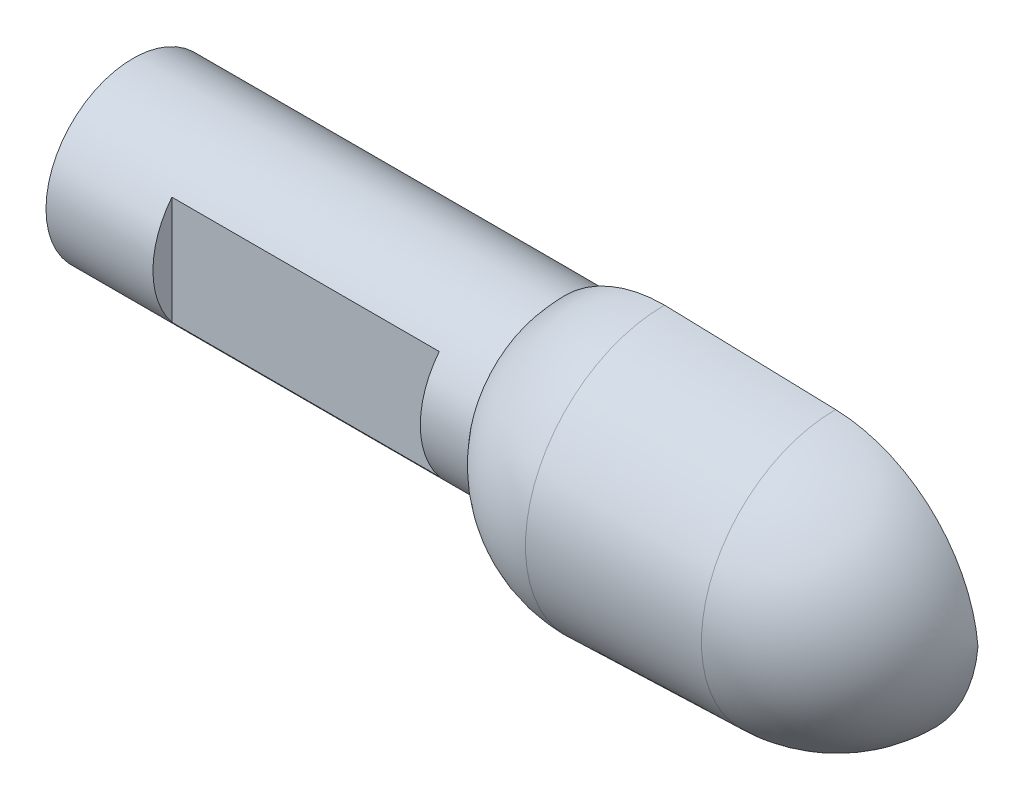
SolidWorks part; units mm, degrees
ref_plane "Front Plane" through (0, 0, 0) normal (0, 0, 1) x (1, 0, 0)
ref_plane "Top Plane" through (0, 0, 0) normal (0, 1, 0) x (1, 0, 0)
ref_plane "Right Plane" through (0, 0, 0) normal (1, 0, 0) x (0, 0, -1)
sketch "Sketch1" plane through (0, 0, 0) normal (0, 0, 1) x (1, 0, 0)
  line L0 (-6.6315, 0) -> (9.1731, 0)
  line L1 (-6.6315, 0) -> (-6.6315, 1.625)
  line L2 (-6.6315, 1.625) -> (1.2685, 1.625)
  line L3 (-10.8216, 0) -> (-13.7944, 0) construction
  line L4 (3.3101, 2.6) -> (6.5101, 2.5087)
  line L7 (43.6251, -16.8667) -> (43.659, -16.9459)
  line L8 (43.659, -16.9459) -> (43.7293, -17.1459)
  arc A0 (1.2685, 1.625) -> (3.3101, 2.6) centre (3.3101, -0.025) cw
  arc A1 (6.5101, 2.5087) -> (9.1731, 0) centre (6.4316, -0.2424) cw
  dimension "D4" = 2.7522
  dimension "D5" = 2.625
  dimension "D1" = 1.625
  dimension "D2" = 3.2
  dimension "D3" = 7.9
sketch "Sketch2" plane through (0, 0, 0) normal (0, 0, 1) x (1, 0, 0)
  line L0 (-6.6315, 0) -> (-6.6315, 1.625)
  line L1 (-6.6315, 1.625) -> (1.2685, 1.625)
  line L3 (3.3101, 2.6) -> (6.5101, 2.5087)
  line L5 (9.1731, 0) -> (-6.6315, 0)
  line L6 (-13.7944, 0) -> (-10.8216, 0) construction
  arc A0 (1.2685, 1.625) -> (3.3101, 2.6) centre (3.3101, -0.025) cw
  arc A1 (6.5101, 2.5087) -> (9.1731, 0) centre (6.4316, -0.2424) cw
revolve "Revolve1" add sketch "Sketch2" angle 360 about L6
ref_plane "Plane2" through (-6.6315, 0, 0) normal (-1, 0, 0) x (0, 0, 1)
sketch "Sketch8" plane through (-6.6315, 0, 0) normal (-1, 0, 0) x (0, 0, 1)
  line L0 (0, -1.625) -> (0, -2.6)
  line L1 (0, 1.625) -> (0, 2.6)
  circle A0 centre (0, 0) radius 1.625 construction
  circle A1 centre (0, 0) radius 1.625 construction
  circle A2 centre (0, 0) radius 2.6 construction
  arc A3 (0, 1.625) -> (0, -1.625) centre (0, 0) ccw
  arc A4 (0, 2.6) -> (0, -2.6) centre (0, 0) ccw
extrude "Cut-Extrude3" cut sketch "Sketch8" against normal through all
ref_plane "Plane3" through (0, 0, 0) normal (0, 0, -1) x (-1, 0, 0)
sketch "Sketch9" plane through (0, 0, 0) normal (0, 0, -1) x (-1, 0, 0)
  line L1 (-1.2685, 1.625) -> (-1.2685, -1.625)
  line L2 (-1.2685, -1.625) -> (-2.0144, -1.625)
  line L4 (-1.994, 1.625) -> (-1.2685, 1.625)
  line L5 (-7.8593, 1.625) -> (-8.4533, 1.625)
  line L6 (-8.4533, -1.625) -> (-7.8593, -1.625)
  arc A0 (-7.8593, 1.625) -> (-1.994, 1.625) centre (-4.9266, -11.3387) cw
  arc A1 (-7.8593, -1.625) -> (-2.0144, -1.625) centre (-4.9368, 13.5505) ccw
  arc A4 (-8.4533, 1.625) -> (-8.4533, -1.625) centre (-7.3546, 0) ccw
extrude "Cut-Extrude4" cut sketch "Sketch9" along normal through all
ref_plane "Plane4" through (0, 0, 0) normal (0, 0, -1) x (-1, 0, 0)
sketch "Sketch10" plane through (0, 0, 0) normal (0, 0, -1) x (-1, 0, 0)
  line L0 (-1.8428, 0) -> (-9.1731, 0) construction
  line L3 (-6.7546, 1.9629) -> (-2.9436, 1.9629)
  line L5 (-6.7546, -1.9629) -> (-2.9436, -1.9629)
  arc A3 (-2.9436, -1.9629) -> (-2.9436, 1.9629) centre (-4.265, 0) ccw
  arc A4 (-6.7546, 1.9629) -> (-6.7546, -1.9629) centre (-6.4245, 0) ccw
extrude "Cut-Extrude5" cut sketch "Sketch10" against normal blind 1 draft 25
sketch "Sketch11" plane through (1.2685, 0, 0) normal (1, 0, 0) x (0, 0, -1)
ref_plane "Plane5" through (-6.6315, 0, 0) normal (-1, 0, 0) x (0, 0, 1)
sketch "Sketch13" plane through (-6.6315, 0, 0) normal (-1, 0, 0) x (0, 0, 1)
  line L0 (1.2706, -1.013) -> (1.2706, 1.013)
  circle A0 centre (0, 0) radius 1.625 construction
  arc A1 (0, -1.625) -> (0, 1.625) centre (0, 0) ccw construction
  arc A2 (1.2706, 1.013) -> (1.2706, -1.013) centre (0, 0) cw
extrude "Cut-Extrude7" cut sketch "Sketch13" against normal blind 5 from offset 2 offset against normal yes
ref_plane "Plane6" through (1.2685, 0, 0) normal (1, 0, 0) x (0, 0, -1)
sketch "Sketch14" plane through (1.2685, 0, 0) normal (1, 0, 0) x (0, 0, -1)
  line L0 (1.1535, 1.1446) -> (1.1535, -1.1446)
  arc A0 (0, -1.625) -> (0, 1.625) centre (0, 0) ccw construction
  arc A1 (1.1535, 1.1446) -> (1.1535, -1.1446) centre (0, 0) cw
extrude "Cut-Extrude8" cut sketch "Sketch14" against normal blind 6 from offset 1
